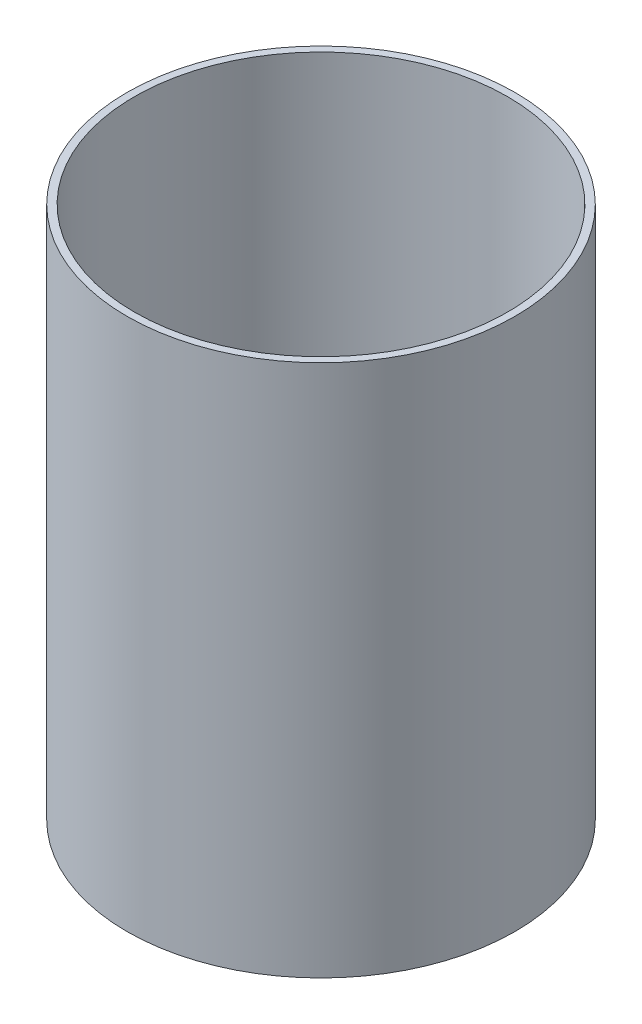
SolidWorks part; units mm, degrees
ref_plane "Front Plane" through (0, 0, 0) normal (0, 0, 1) x (1, 0, 0)
ref_plane "Top Plane" through (0, 0, 0) normal (0, 1, 0) x (1, 0, 0)
ref_plane "Right Plane" through (0, 0, 0) normal (1, 0, 0) x (0, 0, -1)
sketch "Sketch1" plane through (0, 0, 0) normal (0, 1, 0) x (1, 0, 0)
  circle A0 centre (0, 0) radius 132
  circle A1 centre (0, 0) radius 127
  dimension "D1" = 254
  dimension "D2" = 5
extrude "Boss-Extrude1" add sketch "Sketch1" along normal blind 355.6
sketch "Sketch2" plane through (0, 0, 0) normal (0, -1, 0) x (1, 0, 0)
  circle A1 centre (0, 0) radius 132
  circle A2 centre (0, 0) radius 132
  dimension "D1" = 0
extrude "Boss-Extrude2" add sketch "Sketch2" along normal blind 7
sketch "Sketch3" plane through (0, -7, 0) normal (0, -1, 0) x (1, 0, 0)
  line L0 (0, 0) -> (-14.05, 0) construction
  line L1 (-14.05, 5) -> (-14.05, 0) construction
  line L2 (0, 0) -> (34.45, 0) construction
  line L3 (34.45, 0) -> (34.45, 5) construction
  line L5 (-10.05, 10) -> (30, 10)
  line L6 (-10.05, 10) -> (-10.05, -10)
  line L7 (-10.05, -10) -> (30, -10)
  line L8 (30, 10) -> (30, -10)
  circle A1 centre (-14.05, 5) radius 2
  circle A2 centre (-14.05, -5) radius 2
  circle A3 centre (34.45, 5) radius 2
  circle A4 centre (34.45, -5) radius 2
  point P16 (-10.05, 0)
  dimension "D1" = 40.05
  dimension "D2" = 4
  dimension "D3" = 4
  dimension "D4" = 10
  dimension "D5" = 14.05
  dimension "D6" = 5
  dimension "D7" = 34.45
  dimension "D8" = 5
  dimension "D9" = 20
  dimension "D10" = 4
extrude "Cut-Extrude1" cut sketch "Sketch3" against normal through all
sketch "Sketch4" plane through (0, 0, 0) normal (0, 1, 0) x (1, 0, 0)
  circle A0 centre (0, 0) radius 69.85 construction
  circle A1 centre (-69.85, 0) radius 47.5
  dimension "D1" = 139.7
  dimension "D2" = 95
extrude "Cut-Extrude2" cut sketch "Sketch4" against normal through all
sketch "Sketch5" plane through (0, -7, 0) normal (0, -1, 0) x (1, 0, 0)
  line L0 (-69.85, 0) -> (-30.6056, 39.2444) construction
  line L1 (-69.85, 0) -> (-69.85, 41.7202) construction
  circle A0 centre (-69.85, 0) radius 55.5 construction
  circle A1 centre (-30.6056, 39.2444) radius 2
  circle A2 centre (-69.85, 0) radius 55.5 construction
  circle A3 centre (-30.6056, -39.2444) radius 2
  circle A4 centre (-109.0944, 39.2444) radius 2
  circle A5 centre (-109.0944, -39.2444) radius 2
  point P11 (-69.85, 0)
  point P14 (0, 0)
  point P15 (0, 0)
  point P16 (0, 0)
  point P17 (0, 0)
  dimension "D1" = 111
  dimension "D2" = 4
  dimension "D4" = 45
  dimension "D3" = 2
extrude "Cut-Extrude3" cut sketch "Sketch5" against normal through all
